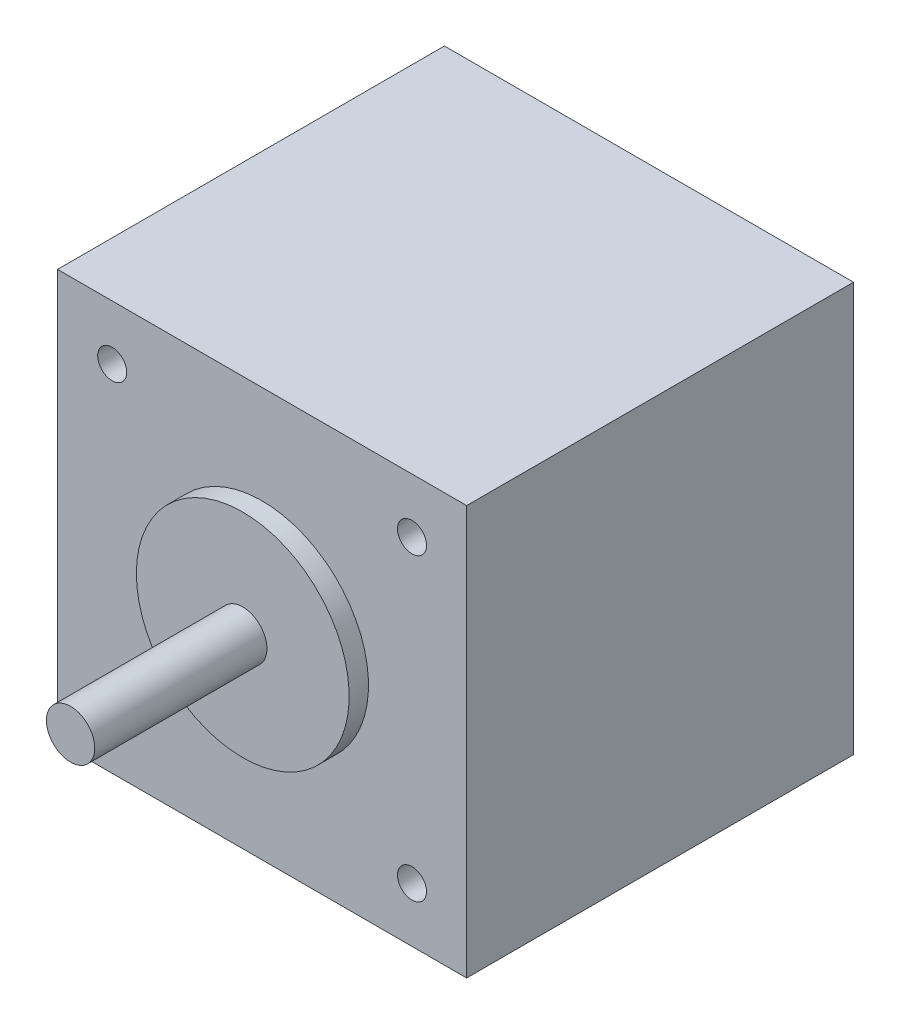
SolidWorks part; units mm, degrees
ref_plane "Спереди" through (0, 0, 0) normal (0, 0, 1) x (1, 0, 0)
ref_plane "Сверху" through (0, 0, 0) normal (0, 1, 0) x (1, 0, 0)
ref_plane "Справа" through (0, 0, 0) normal (1, 0, 0) x (0, 0, -1)
other "Configuration Table"
sketch "Эскиз1" plane through (0, 0, 0) normal (0, 0, 1) x (1, 0, 0)
  line L1 (-21.15, -21.15) -> (21.15, -21.15)
  line L2 (-21.15, -21.15) -> (-21.15, 21.15)
  line L3 (-21.15, 21.15) -> (21.15, 21.15)
  line L4 (21.15, -21.15) -> (21.15, 21.15)
  line L5 (-21.15, -21.15) -> (21.15, 21.15) construction
  line L6 (-21.15, 21.15) -> (21.15, -21.15) construction
  point P0 (0, 0)
  dimension "D1" = 42.3
  dimension "D2" = 42.3
extrude "Корпус" add sketch "Эскиз1" along normal blind 40
sketch "Эскиз2" plane through (0, 0, 0) normal (0, 0, 1) x (1, 0, 0)
  circle A0 centre (0, 0) radius 2.5
  dimension "D1" = 5
extrude "Вал_ПРЕДВ" add sketch "Эскиз2" along normal blind 59.8
sketch "Эскиз3" plane through (0, 0, 0) normal (0, 0, 1) x (1, 0, 0)
  circle A0 centre (0, 0) radius 11
  dimension "D1" = 22
extrude "Буртик_ПРЕДВ" add sketch "Эскиз3" along normal blind 42
sketch "Эскиз4" plane through (0, 0, 0) normal (0, 0, 1) x (1, 0, 0)
  circle A0 centre (0, 0) radius 8
  dimension "D1" = 16
sketch "Эскиз5" plane through (0, 0, 0) normal (0, 0, 1) x (1, 0, 0)
  circle A0 centre (-15.5, -15.5) radius 1.5
  circle A1 centre (-15.5, 15.5) radius 1.5
  circle A2 centre (15.5, -15.5) radius 1.5
  circle A3 centre (15.5, 15.5) radius 1.5
  dimension "D1" = 3
  dimension "D2" = 3
  dimension "D3" = 3
  dimension "D4" = 3
extrude "Крепеж_М3_ПРЕДВ" cut sketch "Эскиз5" against normal blind 4.5 from offset 40
equation "\"Мотор X ширина корпуса\"= 42.3"
equation "\"Мотор X высота корпуса\"= 42.3"
equation "\"Мотор X длина корпуса\"= 40"
equation "\"Мотор X вылет вала\"= 19.8"
equation "\"Мотор Y ширина корпуса\"= 42.3"
equation "\"Мотор Y высота корпуса\"= 42.3"
equation "\"Мотор Y длина корпуса\"= 48"
equation "\"Мотор Y вылет вала\"= 30"
equation "\"Мотор Z ширина корпуса\"= 42"
equation "\"Мотор Z высота корпуса\"= 42"
equation "\"Мотор Z длина корпуса\"= 40"
equation "\"Мотор Z вылет вала\"= 23"
equation "\"Мотор диаметр вала ПРЕДВ\"= 5"
equation "\"Мотор шаг крепления ПРЕДВ\"= 31"
equation "\"Мотор диаметр отверстий ПРЕДВ\"= 3"
equation "\"Мотор глубина отверстий ПРЕДВ\"= 4.5"
equation "\"Мотор диаметр буртика ПРЕДВ\"= 22"
equation "\"Мотор высота буртика ПРЕДВ\"= 2"
equation "\"Мотор диаметр шкива ПРЕДВ\"= 16"
equation "\"Мотор длина шкива ПРЕДВ\"= 12"
equation "\"Мотор отступ шкива ПРЕДВ\"= 5"
equation "\"Мотор X шаг градусов\"= 1.8"
equation "\"Мотор Y шаг градусов\"= 1.8"
equation "\"Мотор Z шаг градусов\"= 1.8"
equation "\"Мотор Y диаметр ротора\"= 25.78"
equation "\"D1@Эскиз1\" = \"Мотор X ширина корпуса\""
equation "\"D1@Корпус\" = \"Мотор X длина корпуса\""
equation "\"D1@Эскиз2\" = \"Мотор диаметр вала ПРЕДВ\""
equation "\"D1@Вал_ПРЕДВ\" = \"Мотор X длина корпуса\" + \"Мотор X вылет вала\""
equation "\"D1@Эскиз3\" = \"Мотор диаметр буртика ПРЕДВ\""
equation "\"D1@Буртик_ПРЕДВ\" = \"Мотор X длина корпуса\" + \"Мотор высота буртика ПРЕДВ\""
equation "\"D1@Эскиз4\" = \"Мотор диаметр шкива ПРЕДВ\""
equation "\"D1@Эскиз5\" = \"Мотор диаметр отверстий ПРЕДВ\""
equation "\"D2@Эскиз5\" = \"Мотор диаметр отверстий ПРЕДВ\""
equation "\"D3@Эскиз5\" = \"Мотор диаметр отверстий ПРЕДВ\""
equation "\"D4@Эскиз5\" = \"Мотор диаметр отверстий ПРЕДВ\""
equation "\"D1@Крепеж_М3_ПРЕДВ\" = \"Мотор глубина отверстий ПРЕДВ\""
equation "\"D19@Крепеж_М3_ПРЕДВ\" = \"Мотор X длина корпуса\""
equation "\"Ширина груза\"= 160"
equation "\"Глубина груза\"= 240"
equation "\"Высота груза\"= 160"
equation "\"Ширина ячейки\"= \"Ширина груза\" + 10"
equation "\"Глубина ячейки\"= \"Глубина груза\" + 10"
equation "\"Высота ячейки\"= \"Высота груза\" + 10 + 13"
equation "\"Колво ячеек ширина\"= 2"
equation "\"Колво ячеек высота\"= 2"
equation "\"Толщина стенки\"= \"Толщина тонких панелей\""
equation "\"Крепление дверцы\"= 5 "
equation "\"Ширина рейки\"= \"Толщина шестерни\""
equation "\"Высота рейки\"= 20"
equation "\"Высота пола\"= 2*\"Толщина тонких панелей\""
equation "\"Колво полозьев\"= 5"
equation "\"Отступ рейки\"= 20"
equation "\"Глубина каретки\"= \"Глубина ячейки\" + 30 + \"Мотор Y высота корпуса\" + 20"
equation "\"Отступ шпильки\"= 26"
equation "\"Диаметр шпильки\"= 5"
equation "\"Длинна шпильки\"= (\"Высота ячейки\"+\"Толщина горизонтальных плит\"+\"Высота пола\")*\"Колво ячеек высота\"+2*(\"Толщина горизонтальных плит\"+\"Отступ рейки\")"
equation "\"Ширина пластины\"= 50  "
equation "\"Высота зона выгрузки\"= \"Высота ячейки\" * 2 + \"Толщина стенки\" * 2"
equation "\"Колво выгрузки\"= 1"
equation "\"Отступ крепления мотора фиксации\"= (\"Ширина пластины\"+20-\"Толщина вертикальных стенок\")/2"
equation "\"Диаметр оси\"= 10"
equation "\"Диаметр ролика\"= 20"
equation "\"Колво роликов\"= 10"
equation "\"Шаг роликов\"= \"Диаметр ролика\" + 20"
equation "\"Ширина ячейки выгрузки\"= \"Ширина ячейки\"+\"Толщина вертикальных стенок\"+2*\"Отступ крепления мотора фиксации\""
equation "\"Длинна рейки\"= (\"Ширина ячейки\"+\"Толщина вертикальных стенок\"+\"Крепление дверцы\")*\"Колво ячеек ширина\"+\"Ширина ячейки выгрузки\"*\"Колво выгрузки\"+\"Толщина вертикальных стенок\"+2*\"Отступ крепления мотора фиксации\"-\"Крепление дверцы\"*\"Колво ячеек ширина\""
equation "\"Толщина шестерни\"= 10"
equation "\"Толщина тонких панелей\"= 6"
equation "\"Толщина вертикальных стенок\"= 6"
equation "\"Толщина горизонтальных плит\"= 6"
equation "\"Базовая высота корпуса\"= (\"Высота ячейки\"+\"Толщина тонких панелей\"+\"Высота пола\")*\"Колво ячеек высота\"+6*\"Толщина тонких панелей\"+\"Мотор X ширина корпуса\"+\"Мотор Y ширина корпуса\"+75"
equation "\"Высота корпуса\"= (\"Высота ячейки\"+\"Толщина горизонтальных плит\"+\"Высота пола\")*\"Колво ячеек высота\"+2*\"Толщина горизонтальных плит\"+4*\"Толщина тонких панелей\"+\"Мотор X ширина корпуса\"+\"Мотор Y ширина корпуса\"+75"
equation "\"Смещение центра корпуса\"= (\"Высота корпуса\"-\"Базовая высота корпуса\")/2-(\"Толщина горизонтальных плит\"-\"Толщина тонких панелей\")"
equation "\"Отметка пола\"= -\"Базовая высота корпуса\"/2+\"Толщина тонких панелей\""
equation "\"Отметка потолка\"= \"Отметка пола\"+\"Высота корпуса\"-2*\"Толщина горизонтальных плит\""
equation "\"Отметка верхней полки\"= \"Отметка потолка\"-(28+\"Толщина тонких панелей\")-\"Высота ячейки\"-\"Высота пола\""
equation "\"Отметка нижней полки\"= \"Отметка верхней полки\"-\"Высота ячейки\"-\"Высота пола\"-\"Толщина горизонтальных плит\""
